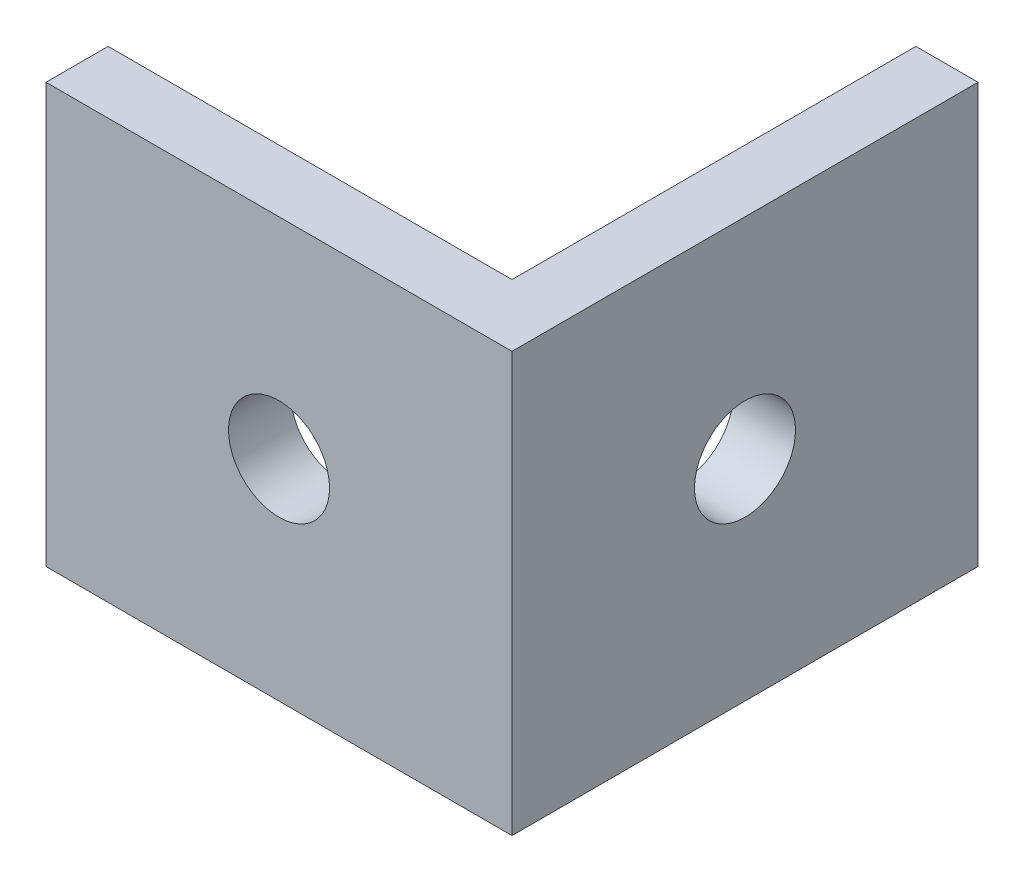
SolidWorks part; units mm, degrees
material "6061 合金"
ref_plane "前视基准面" through (0, 0, 0) normal (0, 0, 1) x (1, 0, 0)
ref_plane "上视基准面" through (0, 0, 0) normal (0, 1, 0) x (1, 0, 0)
ref_plane "右视基准面" through (0, 0, 0) normal (1, 0, 0) x (0, 0, -1)
other "Configuration Table"
sketch "草图1" plane through (0, 0, 0) normal (0, 1, 0) x (1, 0, 0)
  line L0 (0, 0) -> (0, 30)
  line L1 (0, 30) -> (-4, 30)
  line L2 (-4, 30) -> (-4, 4)
  line L3 (-4, 4) -> (-30, 4)
  line L4 (-30, 4) -> (-30, 0)
  line L5 (-30, 0) -> (0, 0)
  point P3 (0, 0)
  dimension "D1" = 4
  dimension "D2" = 30
extrude "凸台-拉伸1" add sketch "草图1" along normal blind 27
sketch "草图2" plane through (0, 0, -4) normal (0, 0, -1) x (-1, 0, 0)
  line L0 (30, 27) -> (30, 0) construction
  line L1 (4, 27) -> (30, 27) construction
  circle A0 centre (15, 13.5) radius 3.25
  dimension "D2" = 6.5
  dimension "D1" = 15
  dimension "D3" = 13.5
extrude "切除-拉伸1" cut sketch "草图2" against normal blind 27
sketch "草图3" plane through (0, 0, 0) normal (1, 0, 0) x (0, 0, -1)
  line L0 (30, 27) -> (30, 0) construction
  circle A0 centre (15, 13.5) radius 3.25
  point P4 (30, 13.5)
  dimension "D1" = 15
  dimension "D2" = 6.5
extrude "切除-拉伸2" cut sketch "草图3" against normal blind 27
